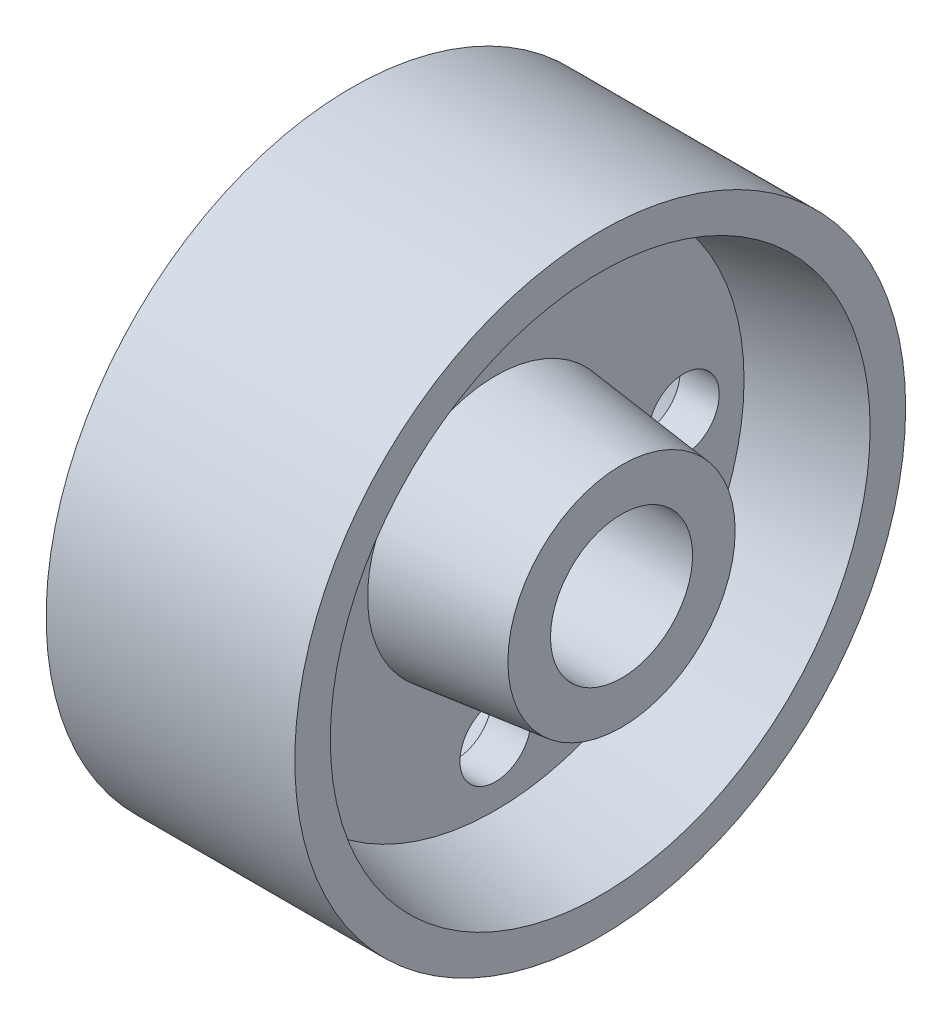
SolidWorks part; units mm, degrees
ref_plane "Front Plane" through (0, 0, 0) normal (0, 0, 1) x (1, 0, 0)
ref_plane "Top Plane" through (0, 0, 0) normal (0, 1, 0) x (1, 0, 0)
ref_plane "Right Plane" through (0, 0, 0) normal (1, 0, 0) x (0, 0, -1)
sketch "Sketch1" plane through (0, 0, 0) normal (0, 1, 0) x (1, 0, 0)
  line L0 (0, 0) -> (0, 43) construction
  line L1 (-56.142, 0) -> (49.4444, 0) construction
  line L2 (20.5, 0) -> (-20.5, 0)
  line L3 (-20.5, 0) -> (-20.5, 16)
  line L4 (17.5, 43) -> (-17.5, 43)
  line L5 (-17.5, 43) -> (-17.5, 38)
  line L6 (-2.75, 35) -> (-2.75, 18)
  line L7 (-20.5, 16) -> (-2.75, 18)
  line L8 (-17.5, 38) -> (-2.75, 35)
  line L9 (20.5, 0) -> (20.5, 16)
  line L10 (20.5, 16) -> (2.75, 18)
  line L11 (2.75, 35) -> (2.75, 18)
  line L12 (17.5, 38) -> (2.75, 35)
  line L13 (17.5, 43) -> (17.5, 38)
  dimension "D1" = 20.5
  dimension "D2" = 16
  dimension "D3" = 17.5
  dimension "D4" = 5
  dimension "D5" = 5.5
  dimension "D6" = 18
  dimension "D7" = 35
  dimension "D8" = 43
revolve "Revolve1" add sketch "Sketch1" angle 360 about L2
sketch "Sketch2" plane through (-20.5, 0, 0) normal (-1, 0, 0) x (0, 0, 1)
  circle A0 centre (0, 0) radius 10
  circle A1 centre (0, 0) radius 26.5 construction
  dimension "D1" = 20
  dimension "D2" = 53
sketch "Sketch4" plane through (-20.5, 0, 0) normal (-1, 0, 0) x (0, 0, 1)
  line L0 (0, 0) -> (0, 26.5) construction
  circle A0 centre (0, 26.5) radius 5
  circle A1 centre (0, 0) radius 26.5 construction
  circle A2 centre (26.5, 0) radius 5
  circle A3 centre (0, -26.5) radius 5
  circle A4 centre (-26.5, 0) radius 5
  point P5 (-29.9725, -6.7285)
  point P7 (0, 0)
  point P15 (0, 0)
  dimension "D1" = 10
  dimension "D2" = 4
extrude "Cut-Extrude1" cut sketch "Sketch4" against normal through all both and the other way through all
sketch "Sketch5" plane through (-20.5, 0, 0) normal (-1, 0, 0) x (0, 0, 1)
  circle A0 centre (0, 0) radius 10
extrude "Cut-Extrude2" cut sketch "Sketch5" against normal through all both
